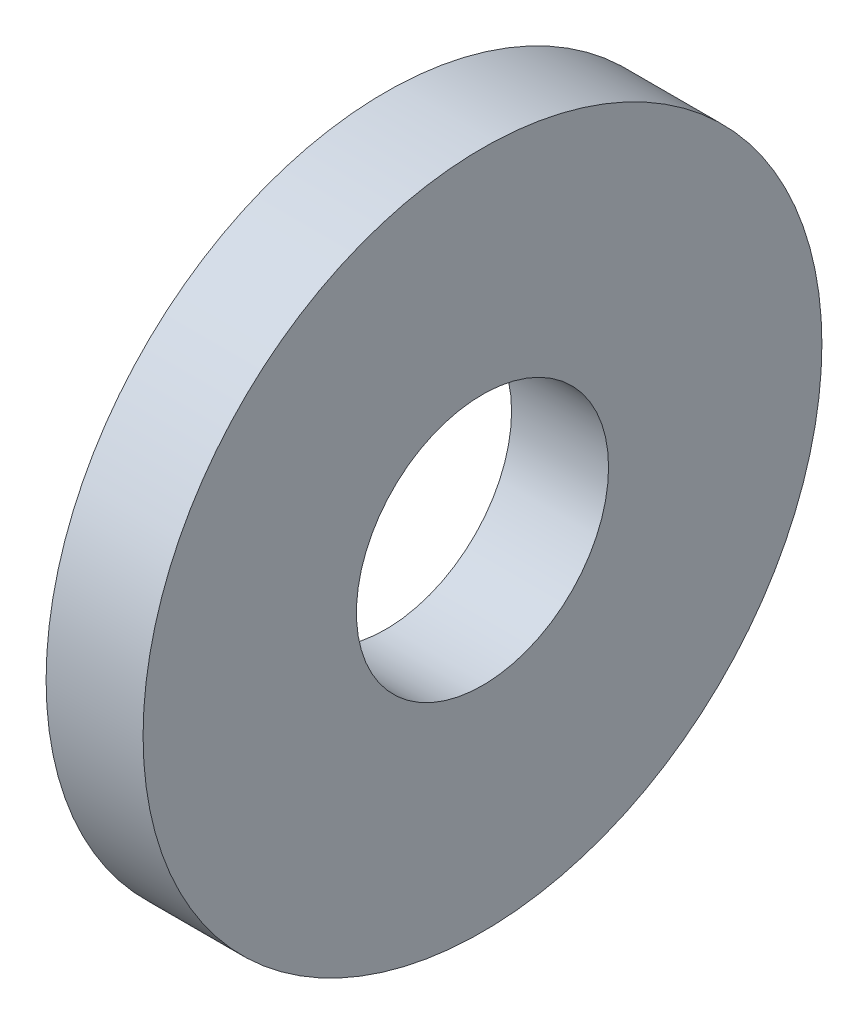
SolidWorks part; units mm, degrees
ref_plane "Plane1" through (0, 0, 0) normal (0, 0, 1) x (1, 0, 0)
ref_plane "Plane2" through (0, 0, 0) normal (0, 1, 0) x (1, 0, 0)
ref_plane "Plane3" through (0, 0, 0) normal (1, 0, 0) x (0, 0, -1)
sketch "Sketch1" plane through (0, 0, 0) normal (1, 0, 0) x (0, 0, -1)
  circle A0 centre (0.5737, -0.8606) radius 17.5
  circle A1 centre (0.5737, -0.8606) radius 6.5
  dimension "OutsideDia" = 35
  dimension "Insid_Dia" = 13
extrude "Base-Extrude" add sketch "Sketch1" along normal blind 5
